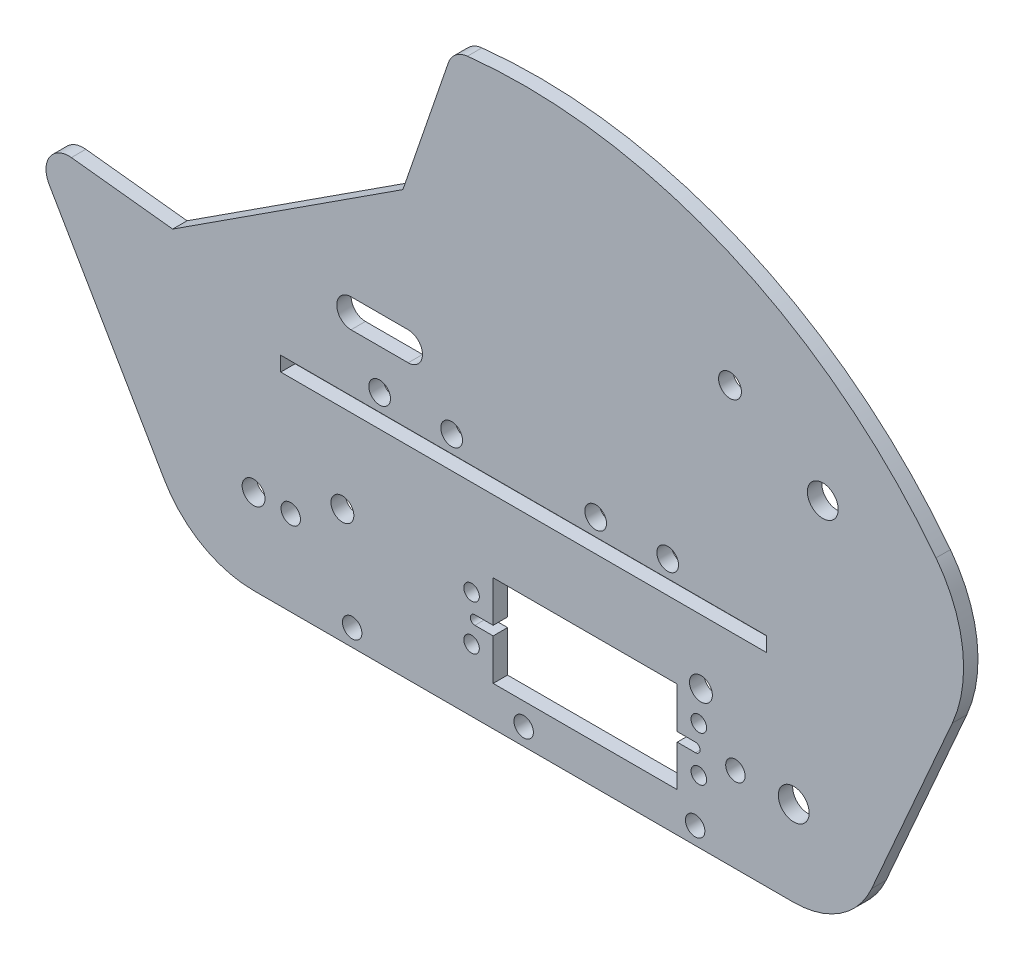
SolidWorks part; units mm, degrees
ref_plane "Front Plane" through (0, 0, 0) normal (0, 0, 1) x (1, 0, 0)
ref_plane "Top Plane" through (0, 0, 0) normal (0, 1, 0) x (1, 0, 0)
ref_plane "Right Plane" through (0, 0, 0) normal (1, 0, 0) x (0, 0, -1)
sketch "Sketch1" plane through (0, 0, 0) normal (0, 0, 1) x (1, 0, 0)
  line L8 (0, 18.9078) -> (120.015, 18.9078) construction
  line L18 (155.2575, 52.1157) -> (-35.2425, 52.1157) construction
  line L37 (0, 0) -> (120.015, 0)
  line L54 (155.2575, 52.1157) -> (137.3256, 11.3022)
  line L55 (60.0075, 52.1157) -> (60.0075, 18.9078) construction
  line L56 (-35.2425, 52.1157) -> (-17.3106, 11.3022)
  line L57 (0, 18.9078) -> (19.7347, 25.5664) construction
  line L59 (151.631, 82.096) -> (-31.616, 82.096) construction
  circle A21 centre (120.015, 18.9078) radius 3.429
  circle A22 centre (0, 18.9078) radius 2.54
  circle A24 centre (19.7347, 25.5664) radius 2.54
  arc A25 (137.3256, 11.3022) -> (120.015, 0) centre (120.015, 18.9078) cw
  arc A26 (0, 0) -> (-17.3106, 11.3022) centre (0, 18.9078) cw
  arc A28 (151.631, 82.096) -> (-31.616, 82.096) centre (60.0075, 11.7572) ccw
  arc A29 (151.631, 82.096) -> (155.2575, 52.1157) centre (128.1135, 64.0417) cw
  arc A30 (-31.616, 82.096) -> (-35.2425, 52.1157) centre (-8.0985, 64.0417) ccw
  dimension "D5" = 18.9078
  dimension "D8" = 183.2469
  dimension "D3" = 52.1157
  dimension "D11" = 6.858
  dimension "D10" = 5.08
  dimension "D1" = 190.5
  dimension "D4" = 18.645
  dimension "D6" = 20.8278
  dimension "D7" = 120.015
  dimension "D9" = 29.9803
extrude "Boss-Extrude1" add sketch "Sketch1" along normal blind 3.2004
sketch "Sketch2" plane through (0, 0, 0) normal (0, 0, -1) x (-1, 0, 0)
  line L1 (-155.2575, 52.1157) -> (35.2425, 52.1157) construction
  line L28 (-92.0115, 52.1157) -> (-76.0095, 52.1157) construction
  line L29 (-76.0095, 52.1157) -> (-44.0055, 52.1157) construction
  line L30 (-44.0055, 52.1157) -> (-28.0035, 52.1157) construction
  circle A0 centre (-92.0115, 52.1157) radius 2.413
  circle A1 centre (-76.0095, 52.1157) radius 2.413
  circle A2 centre (-44.0055, 52.1157) radius 2.413
  circle A3 centre (-28.0035, 52.1157) radius 2.413
  point P11 (-36.0045, 52.1157)
  point P16 (-84.0105, 52.1157)
  dimension "D3" = 4.826
  dimension "D2" = 16.002
  dimension "D4" = 48.006
extrude "Cut-Extrude1" cut sketch "Sketch2" against normal blind 3.2004
sketch "Sketch5" plane through (0, 0, 0) normal (0, 0, -1) x (-1, 0, 0)
  line L0 (0, 18.9078) -> (-120.015, 18.9078) construction
  line L5 (-73.682, 29.0678) -> (-73.682, 8.7478) construction
  line L6 (-53.235, 29.0678) -> (-53.235, 8.7478)
  line L10 (-94.129, 8.7478) -> (-94.129, 29.0678)
  line L13 (-98.932, 13.9078) -> (-98.932, 23.9078) construction
  line L14 (-48.432, 13.9078) -> (-48.432, 23.9078) construction
  line L15 (-98.932, 18.9078) -> (-48.432, 18.9078) construction
  line L21 (-94.129, 8.7478) -> (-53.235, 8.7478)
  line L25 (-94.129, 29.0678) -> (-53.235, 29.0678)
  circle A0 centre (-98.932, 23.9078) radius 1.7272
  circle A1 centre (-48.432, 13.9078) radius 1.7272
  circle A2 centre (-48.432, 23.9078) radius 1.7272
  circle A3 centre (-98.932, 13.9078) radius 1.7272
  circle A6 centre (-120.015, 18.9078) radius 3.429 construction
  point P0 (-83.532, 18.9078)
  point P1 (-120.015, 18.9078)
  point P4 (-73.682, 18.9078)
  dimension "D2" = 20.32
  dimension "D3" = 3.4544
  dimension "D1" = 50.5
  dimension "D4" = 40.894
  dimension "D5" = 15.4
  dimension "D6" = 10
extrude "Cut-Extrude3" cut sketch "Sketch5" against normal through all
sketch "Sketch7" plane through (0, 0, 0) normal (0, 0, -1) x (-1, 0, 0)
  line L0 (0, 18.9078) -> (-120.015, 18.9078) construction
  line L1 (-53.235, 8.7478) -> (-53.235, 29.0678) construction
  line L4 (-98.193, 19.9238) -> (-94.129, 19.9238)
  line L5 (-98.193, 19.9238) -> (-98.193, 17.8918) construction
  line L6 (-94.129, 29.0678) -> (-94.129, 8.7478) construction
  line L7 (-98.193, 17.8918) -> (-94.129, 17.8918)
  line L8 (-94.129, 19.9238) -> (-94.129, 17.8918)
  line L9 (-53.235, 19.9238) -> (-49.171, 19.9238)
  line L10 (-53.235, 19.9238) -> (-53.235, 17.8918)
  line L11 (-53.235, 17.8918) -> (-49.171, 17.8918)
  line L12 (-49.171, 19.9238) -> (-49.171, 17.8918) construction
  arc A6 (-49.171, 19.9238) -> (-49.171, 17.8918) centre (-49.171, 18.9078) cw
  arc A7 (-98.193, 19.9238) -> (-98.193, 17.8918) centre (-98.193, 18.9078) ccw
  point P22 (-94.129, 18.9078)
  point P23 (-53.235, 18.9078)
  dimension "D4" = 4.064
  dimension "D5" = 2.032
extrude "Cut-Extrude5" cut sketch "Sketch7" against normal up to surface (3.2004 mm away) up to face at (97.2048, 23.9078, 3.2004)
sketch "Sketch6" plane through (0, 0, 0) normal (0, 0, -1) x (-1, 0, 0)
  line L0 (-99.4008, 30.8094) -> (-120.015, 18.9078) construction
  line L1 (0, 0) -> (-120.015, 0) construction
  circle A1 centre (-19.7347, 25.5664) radius 2.54 construction
  circle A2 centre (-99.4008, 30.8094) radius 2.54
  circle A3 centre (-120.015, 18.9078) radius 3.429 construction
  dimension "D2" = 23.8032
  dimension "D3" = 30
extrude "Cut-Extrude4" cut sketch "Sketch6" against normal through all
sketch "Sketch8" plane through (0, 0, 3.2004) normal (0, 0, 1) x (1, 0, 0)
  line L0 (75.1019, 13.9078) -> (21.7621, 13.9078) construction
  line L1 (53.235, 8.7478) -> (53.235, 17.8918) construction
  circle A0 centre (48.432, 13.9078) radius 1.7272 construction
  point P2 (48.432, 13.9078)
sketch "Sketch9" plane through (0, 0, 3.2004) normal (0, 0, 1) x (1, 0, 0)
  line L0 (21.9075, 3.81) -> (98.1075, 3.81) construction
  line L1 (60.0075, 7.62) -> (60.0075, 0) construction
  line L2 (0, 0) -> (120.015, 0) construction
  circle A0 centre (21.9075, 3.81) radius 2.159
  circle A1 centre (60.0075, 3.81) radius 2.159
  circle A2 centre (98.1075, 3.81) radius 2.159
  point P6 (60.0075, 3.81)
  dimension "D3" = 4.318
  dimension "D1" = 76.2
  dimension "D2" = 7.62
extrude "Cut-Extrude6" cut sketch "Sketch9" against normal up to surface (3.2004 mm away) up to face at (96.8608, 30.8094, 0)
sketch "Sketch10" plane through (0, 0, 3.2004) normal (0, 0, 1) x (1, 0, 0)
  line L0 (60.0075, 55.9257) -> (60.0075, 52.1157) construction
  line L1 (6.0325, 81.3257) -> (113.9825, 81.3257) construction
  line L2 (6.0325, 81.3257) -> (6.0325, 55.9257) construction
  line L3 (6.0325, 55.9257) -> (113.9825, 55.9257) construction
  line L4 (113.9825, 81.3257) -> (113.9825, 55.9257) construction
  line L5 (155.2575, 52.1157) -> (-35.2425, 52.1157) construction
  line L6 (60.0075, 52.1157) -> (60.0075, 48.3057) construction
  line L7 (60.0075, 52.1157) -> (60.0075, 18.9078) construction
  line L8 (6.0325, 48.3057) -> (113.9825, 48.3057)
  line L9 (6.0325, 48.3057) -> (6.0325, 45.0545)
  line L10 (6.0325, 45.0545) -> (113.9825, 45.0545)
  line L11 (113.9825, 48.3057) -> (113.9825, 45.0545)
  dimension "D1" = 25.4
  dimension "D2" = 107.95
  dimension "D3" = 3.81
  dimension "D4" = 7.62
  dimension "D5" = 3.2512
extrude "Cut-Extrude7" cut sketch "Sketch10" against normal up to surface (3.2004 mm away) up to face at (19.7485, 3.81, 0)
sketch "Sketch11" plane through (0, 0, 3.2004) normal (0, 0, 1) x (1, 0, 0)
  line L0 (146.2916, 31.7089) -> (111.6995, 46.9073) construction
  line L1 (111.6995, 46.9073) -> (126.4745, 80.5358) construction
  line L2 (137.3256, 11.3022) -> (155.2575, 52.1157) construction
  line L3 (105.8603, 92.4374) -> (126.4745, 80.5358) construction
  line L5 (6.0325, 81.3257) -> (113.9825, 81.3257) construction
  circle A0 centre (126.4745, 80.5358) radius 3.429
  circle A1 centre (105.8603, 92.4374) radius 2.54
  circle A2 centre (120.015, 18.9078) radius 3.429 construction
  circle A5 centre (19.7347, 25.5664) radius 2.54 construction
  dimension "D1" = 37.7837
  dimension "D2" = 36.7311
  dimension "D3" = 23.8032
  dimension "D4" = 30
extrude "Cut-Extrude8" cut sketch "Sketch11" against normal up to surface (3.2004 mm away) up to face at (60.0075, 46.6801, 0)
sketch "Sketch12" plane through (0, 0, 3.2004) normal (0, 0, 1) x (1, 0, 0)
  line L0 (-32.6149, 80.7753) -> (-17.2714, 56.9367)
  line L1 (-17.2714, 56.9367) -> (38.7942, 93.0228)
  line L2 (38.7942, 93.0228) -> (47.3024, 126.5656)
  line L3 (0, 18.9078) -> (0, 56.9367) construction
  line L4 (0, 56.9367) -> (-17.2714, 56.9367) construction
  line L6 (0, 0) -> (120.015, 0) construction
  arc A1 (47.3024, 126.5656) -> (-32.6149, 80.7753) centre (60.0075, 11.7572) ccw
  circle A3 centre (0, 18.9078) radius 2.54 construction
  arc A4 (151.631, 82.096) -> (-31.616, 82.096) centre (60.0075, 11.7572) ccw construction
  dimension "D1" = 66.675
  dimension "D2" = 137
  dimension "D3" = 28.3497
  dimension "D4" = 38.0289
  dimension "D5" = 17.2714
sketch "Sketch13" plane through (0, 0, 3.2004) normal (0, 0, 1) x (1, 0, 0)
  line L1 (-37.7469, 127.2665) -> (90.0451, 127.2665)
  line L2 (-37.7469, 127.2665) -> (-37.7469, 55.9257)
  line L3 (-37.7469, 55.9257) -> (90.0451, 55.9257)
  line L4 (90.0451, 127.2665) -> (90.0451, 55.9257)
  line L5 (6.0325, 55.9257) -> (113.9825, 55.9257) construction
  arc A0 (151.631, 82.096) -> (-31.616, 82.096) centre (60.0075, 11.7572) ccw construction
  arc A1 (-31.616, 82.096) -> (-35.2425, 52.1157) centre (-8.0985, 64.0417) ccw construction
sketch "Sketch14" plane through (0, 0, 0) normal (0, 0, -1) x (-1, 0, 0)
  line L0 (-44.301, 126.1937) -> (-33.1727, 93.7352)
  line L1 (-33.1727, 93.7352) -> (17.9749, 60.5682)
  line L2 (17.9749, 60.5682) -> (31.7885, 81.8706)
  line L3 (-113.9825, 48.3057) -> (-6.0325, 48.3057) construction
  arc A0 (31.616, 82.096) -> (-151.631, 82.096) centre (-60.0075, 11.7572) ccw construction
  arc A1 (-44.301, 126.1937) -> (31.7885, 81.8706) centre (-60.0075, 11.7572) cw
  dimension "D1" = 141.886
  dimension "D2" = 60.96
  dimension "D3" = 25.3891
  dimension "D4" = 34.3132
  dimension "D5" = 32.962
extrude "Cut-Extrude9" cut sketch "Sketch14" against normal up to surface (3.2004 mm away) up to face at (129.9035, 80.5358, 3.2004)
sketch "Sketch15" plane through (0, 0, 3.2004) normal (0, 0, 1) x (1, 0, 0)
  line L1 (0, 0) -> (120.015, 0) construction
  line L3 (8.255, 18.9078) -> (107.0559, 18.9078) construction
  line L4 (60.0075, 18.9078) -> (60.0075, 0) construction
  circle A2 centre (8.255, 18.9078) radius 2.159
  circle A5 centre (107.0559, 18.9078) radius 2.159
  dimension "D3" = 4.318
  dimension "D4" = 51.7525
  dimension "D5" = 18.9078
  dimension "D6" = 47.0484
extrude "Cut-Extrude10" cut sketch "Sketch15" against normal up to surface (3.2004 mm away) up to face at (49.5814, 52.8698, 0)
sketch "Sketch16" plane through (0, 0, 3.2004) normal (0, 0, 1) x (1, 0, 0)
  line L0 (-45.0411, 54.7574) -> (-19.8272, 11.4052)
  line L1 (-42.0685, 81.7954) -> (-45.0411, 54.7574) construction
  line L2 (0, 0) -> (120.015, 0) construction
  line L3 (-19.8272, 11.4052) -> (0, 0) construction
  line L4 (-35.2425, 52.1157) -> (-17.3106, 11.3022) construction
  line L5 (-35.8384, 88.1161) -> (-17.9749, 60.5682)
  line L6 (-31.7879, 81.8697) -> (-17.9749, 60.5682) construction
  arc A0 (-35.8384, 88.1161) -> (-42.0685, 81.7954) centre (58.563, -11.1634) ccw
  arc A1 (-42.0685, 81.7954) -> (-45.0411, 54.7574) centre (-25.2559, 66.2646) ccw
  arc A2 (-17.9749, 60.5682) -> (0, 0) centre (227.7067, 100.528) ccw
  arc A4 (-19.8272, 11.4052) -> (0, 0) centre (0, 22.9368) ccw
  dimension "D1" = 50.1513
  dimension "D2" = 22.8735
  dimension "D3" = 6.464
  dimension "D4" = 27.2009
  dimension "D5" = 143.544
extrude "Boss-Extrude2" add sketch "Sketch16" against normal up to surface (3.2004 mm away) up to face at (6.096, 18.9078, 0)
fillet "Fillet1" radius 5.08 2 edges at (44.301, 126.1937, 1.6002) (-35.8384, 88.1161, 1.6002)
sketch "Sketch17" plane through (0, 0, 0) normal (0, 0, -1) x (-1, 0, 0)
  line L1 (-34.3535, 67.3557) -> (-21.6535, 67.3557)
  line L2 (-34.3535, 67.3557) -> (-34.3535, 61.0057) construction
  line L3 (-34.3535, 61.0057) -> (-21.6535, 61.0057)
  line L4 (-21.6535, 67.3557) -> (-21.6535, 61.0057) construction
  line L7 (0, 0) -> (-120.015, 0) construction
  arc A0 (-21.6535, 67.3557) -> (-21.6535, 61.0057) centre (-21.6535, 64.1807) cw
  arc A1 (-34.3535, 67.3557) -> (-34.3535, 61.0057) centre (-34.3535, 64.1807) ccw
  circle A5 centre (-28.0035, 52.1157) radius 2.413 construction
  dimension "D3" = 8.89
  dimension "D4" = 6.35
  dimension "D1" = 12.7
  dimension "D2" = 6.35
extrude "Cut-Extrude11" cut sketch "Sketch17" against normal up to surface (3.2004 mm away) up to face at (10.414, 18.9078, 3.2004)
sketch "Sketch18" plane through (0, 0, 0) normal (0, 0, -1) x (-1, 0, 0)
  line L0 (39.398, 93.6054) -> (17.9749, 60.5682)
  line L1 (17.9749, 60.5682) -> (70.5352, 66.4201)
  line L2 (70.5352, 66.4201) -> (39.398, 93.6054)
  line L3 (17.9749, 60.5682) -> (32.4303, 82.8603) construction
extrude "Cut-Extrude12" cut sketch "Sketch18" against normal up to surface (3.2004 mm away) up to face at (28.0035, 64.1807, 3.2004)
fillet "Fillet3" radius 5.08 1 edges at (-48.023, 63.9137, 1.6002)
